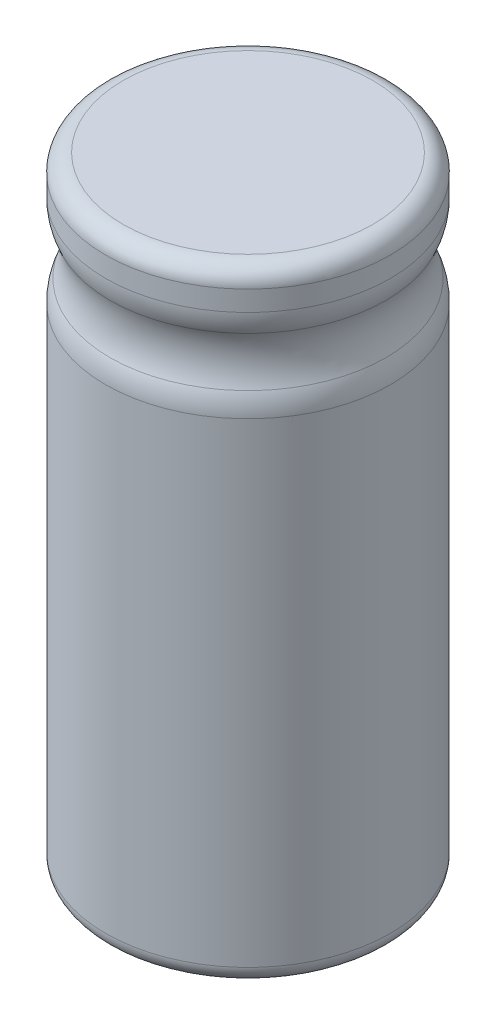
SolidWorks part; units mm, degrees
ref_plane "Front Plane" through (0, 0, 0) normal (0, 0, 1) x (1, 0, 0)
ref_plane "Top Plane" through (0, 0, 0) normal (0, 1, 0) x (1, 0, 0)
ref_plane "Right Plane" through (0, 0, 0) normal (1, 0, 0) x (0, 0, -1)
sketch "Sketch1" plane through (0, 0, 0) normal (0, 1, 0) x (1, 0, 0)
  circle A0 centre (0, 0) radius 16.125
  dimension "D1" = 32.25
extrude "Boss-Extrude1" add sketch "Sketch1" along normal mid plane 70.5
fillet "Fillet1" radius 2 2 edges at (0, -35.25, 16.125) (0, 35.25, 16.125)
sketch "Sketch2" plane through (0, 0, 0) normal (0, 0, 1) x (1, 0, 0)
  line L0 (16.125, -33.25) -> (16.125, 33.25) construction
  line L1 (16.125, 29.5) -> (0, 29.5) construction
  line L2 (0, 33.25) -> (0, -33.25) construction
  line L3 (16.125, 22) -> (0, 22) construction
  line L4 (16.125, 22) -> (16.125, 29.5)
  line L5 (16.125, 29.5) -> (16.125, 22)
  line L6 (0, 35.25) -> (0, 0) construction
  line L7 (14.125, 35.25) -> (-14.125, 35.25) construction
  arc A0 (16.125, 22) -> (16.125, 29.5) centre (22.0358, 25.75) cw
  dimension "D1" = 7
  dimension "D2" = 7.5
  dimension "D3" = 22
revolve "Cut-Revolve1" cut sketch "Sketch2" angle 360 about L6
fillet "Fillet2" radius 6 2 edges at (0, 29.5, 16.125) (0, 22, 16.125)
